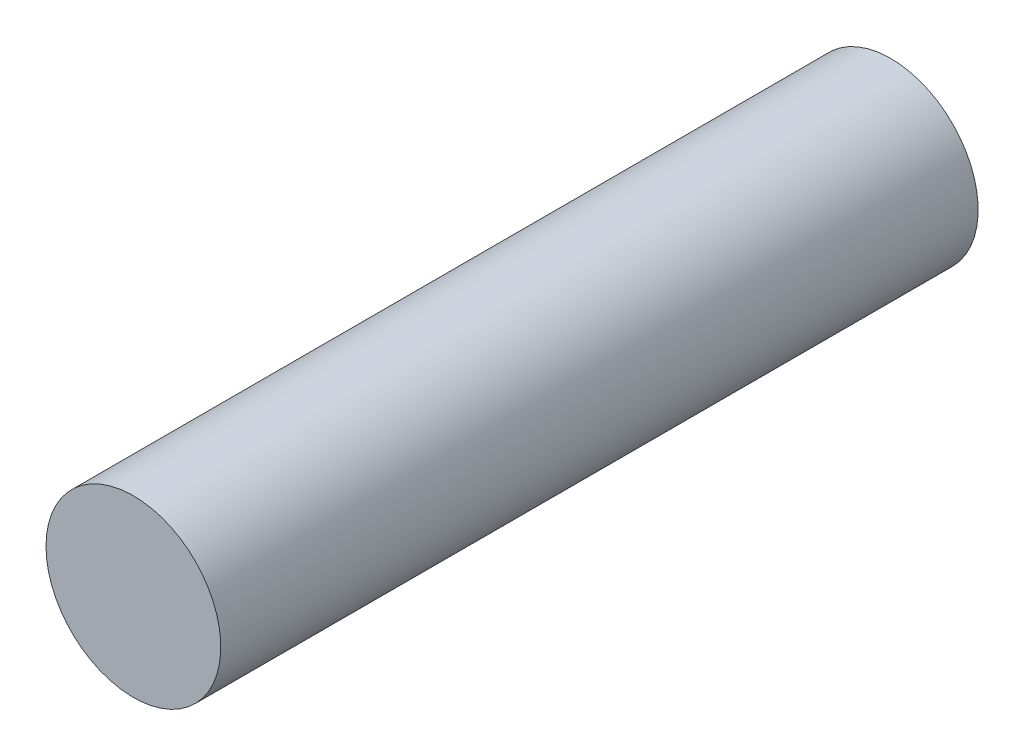
SolidWorks part; units mm, degrees
ref_plane "Front Plane" through (0, 0, 0) normal (0, 0, 1) x (1, 0, 0)
ref_plane "Top Plane" through (0, 0, 0) normal (0, 1, 0) x (1, 0, 0)
ref_plane "Right Plane" through (0, 0, 0) normal (1, 0, 0) x (0, 0, -1)
sketch "Sketch1" plane through (0, 0, 0) normal (0, 0, 1) x (1, 0, 0)
  circle A0 centre (0, 0) radius 6
extrude "Boss-Extrude1" add sketch "Sketch1" along normal blind 52
scale "Scale1" scale about centroid uniform scaling yes scale factor 0.75
scale "Scale2" scale about centroid uniform scaling yes scale factor 0.5
